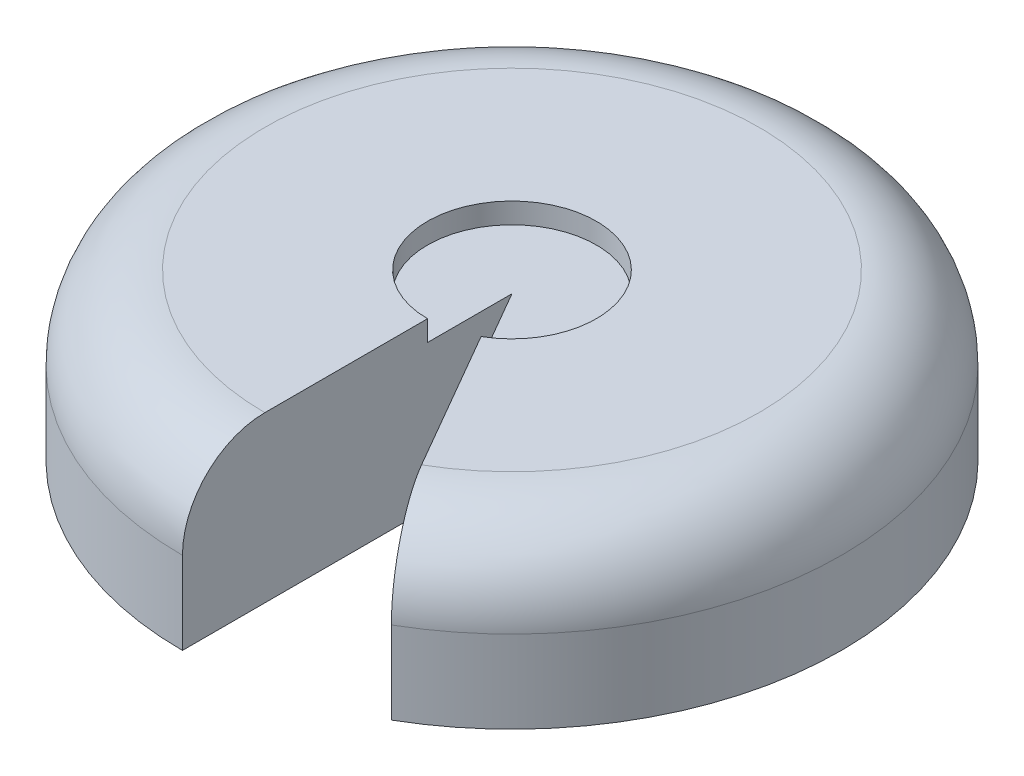
SolidWorks part; units mm, degrees
ref_plane "Front Plane" through (0, 0, 0) normal (0, 0, 1) x (1, 0, 0)
ref_plane "Top Plane" through (0, 0, 0) normal (0, 1, 0) x (1, 0, 0)
ref_plane "Right Plane" through (0, 0, 0) normal (1, 0, 0) x (0, 0, -1)
sketch "Sketch1" plane through (0, 0, 0) normal (0, 1, 0) x (1, 0, 0)
  line L0 (0, 0) -> (0, -40)
  line L1 (0, 0) -> (20, -34.641)
  circle A0 centre (0, 0) radius 40
  arc A1 (0, -40) -> (20, -34.641) centre (0, 0) ccw
extrude "Boss-Extrude1" add sketch "Sketch1" along normal blind 20 contours L1 A0 L0
sketch "Sketch3" plane through (0, 20, 0) normal (0, 1, 0) x (1, 0, 0)
  circle A0 centre (0, 0) radius 10.25
extrude "Cut-Extrude1" cut sketch "Sketch3" against normal blind 2.5
fillet "Fillet1" radius 10 1 edges at (-10.3528, 20, -38.637)
